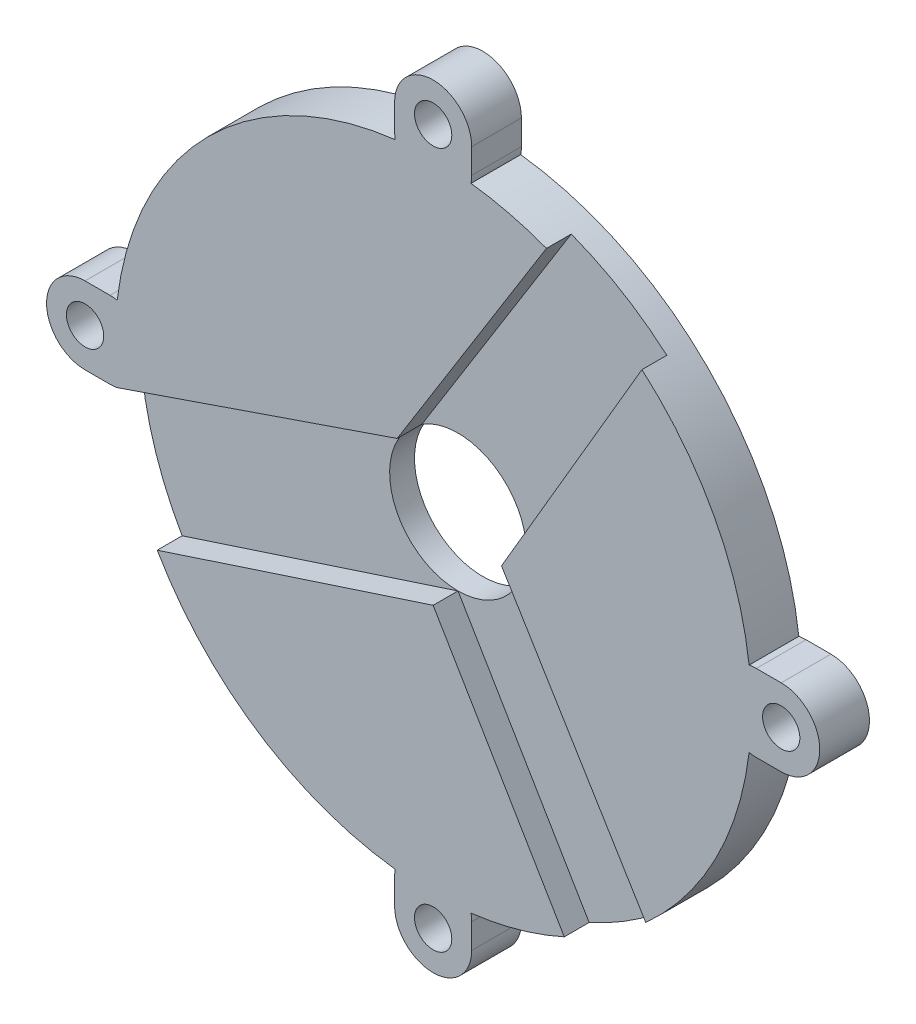
SolidWorks part; units mm, degrees
ref_plane "Front Plane" through (0, 0, 0) normal (0, 0, 1) x (1, 0, 0)
ref_plane "Top Plane" through (0, 0, 0) normal (0, 1, 0) x (1, 0, 0)
ref_plane "Right Plane" through (0, 0, 0) normal (1, 0, 0) x (0, 0, -1)
sketch "Sketch3" plane through (0, 0, 0) normal (0, 0, 1) x (1, 0, 0)
sketch "Sketch4" plane through (0, 0, 0) normal (0, 0, 1) x (1, 0, 0)
  line L0 (28, 3.1) -> (26, 3.1)
  line L1 (3.1, 26) -> (3.1, 28)
  line L2 (-3.1, 28) -> (-3.1, 26)
  line L3 (-26, 3.1) -> (-28, 3.1)
  line L4 (-28, -3.1) -> (-26, -3.1)
  line L5 (-3.1, -26) -> (-3.1, -28)
  line L6 (3.1, -28) -> (3.1, -26)
  line L7 (26, -3.1) -> (28, -3.1)
  circle A0 centre (0, 0) radius 5.5
  circle A1 centre (-28, 0) radius 1.5
  circle A2 centre (0, 28) radius 1.5
  circle A3 centre (28, 0) radius 1.5
  circle A4 centre (0, -28) radius 1.5
  arc A5 (28, -3.1) -> (28, 3.1) centre (28, 0) ccw
  arc A6 (26, 3.1) -> (25.4183, 3.0449) centre (26, 0) ccw
  arc A7 (25.4183, 3.0449) -> (3.0449, 25.4183) centre (0, 0) ccw
  arc A8 (3.0449, 25.4183) -> (3.1, 26) centre (0, 26) ccw
  arc A9 (3.1, 28) -> (-3.1, 28) centre (0, 28) ccw
  arc A10 (-3.1, 26) -> (-3.0449, 25.4183) centre (0, 26) ccw
  arc A11 (-3.0449, 25.4183) -> (-25.4183, 3.0449) centre (0, 0) ccw
  arc A12 (-25.4183, 3.0449) -> (-26, 3.1) centre (-26, 0) ccw
  arc A13 (-28, 3.1) -> (-28, -3.1) centre (-28, 0) ccw
  arc A14 (-26, -3.1) -> (-25.4183, -3.0449) centre (-26, 0) ccw
  arc A15 (-25.4183, -3.0449) -> (-3.0449, -25.4183) centre (0, 0) ccw
  arc A16 (-3.0449, -25.4183) -> (-3.1, -26) centre (0, -26) ccw
  arc A17 (-3.1, -28) -> (3.1, -28) centre (0, -28) ccw
  arc A18 (3.1, -26) -> (3.0449, -25.4183) centre (0, -26) ccw
  arc A19 (3.0449, -25.4183) -> (25.4183, -3.0449) centre (0, 0) ccw
  arc A20 (25.4183, -3.0449) -> (26, -3.1) centre (26, 0) ccw
extrude "Boss-Extrude2" add sketch "Sketch4" along normal blind 4
sketch "Sketch5" plane through (0, 0, 4) normal (0, 0, 1) x (1, 0, 0)
  line L3 (-25.4183, -3.0449) -> (-2.8924, 4.678)
  line L4 (-22.1957, -12.7558) -> (0, -5.5)
  line L5 (9.114, 23.9227) -> (-2.8924, 4.678)
  line L6 (5.5, 0) -> (16.7988, 19.3173)
  line L7 (0, -5.5) -> (10.5499, -23.3251)
  line L8 (5.5, 0) -> (17.1042, -19.0475)
  arc A0 (-25.4183, -3.0449) -> (-3.0449, -25.4183) centre (0, 0) ccw construction
  arc A1 (3.0449, -25.4183) -> (25.4183, -3.0449) centre (0, 0) ccw construction
  arc A2 (25.4183, 3.0449) -> (3.0449, 25.4183) centre (0, 0) ccw construction
  circle A3 centre (0, 0) radius 5.5 construction
  arc A4 (-25.4183, -3.0449) -> (-22.1957, -12.7558) centre (0, 0) ccw
  arc A5 (10.5499, -23.3251) -> (17.1042, -19.0475) centre (0, 0) ccw
  arc A6 (16.7988, 19.3173) -> (9.114, 23.9227) centre (0, 0) ccw
extrude "Cut-Extrude1" cut sketch "Sketch5" against normal blind 2
